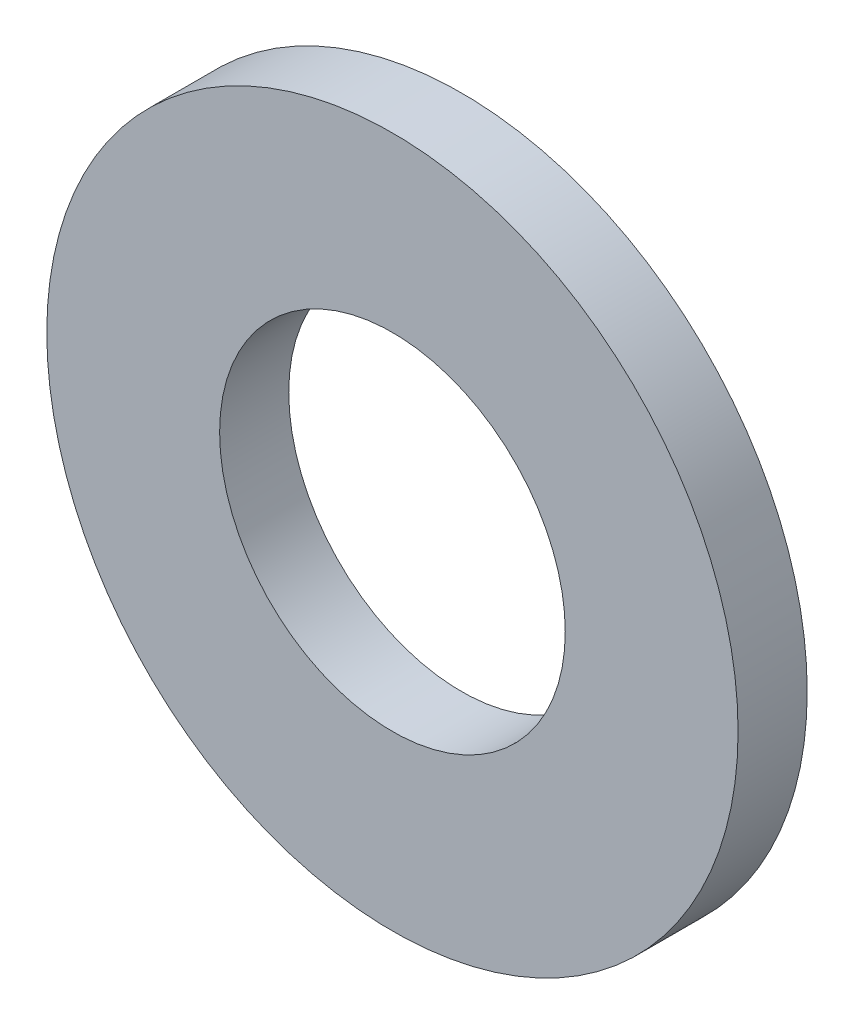
SolidWorks part; units mm, degrees
ref_plane "Front Plane" through (0, 0, 0) normal (0, 0, 1) x (1, 0, 0)
ref_plane "Top Plane" through (0, 0, 0) normal (0, 1, 0) x (1, 0, 0)
ref_plane "Right Plane" through (0, 0, 0) normal (1, 0, 0) x (0, 0, -1)
sketch "Sketch1" plane through (0, 0, 0) normal (0, 0, 1) x (1, 0, 0)
  circle A0 centre (0, 0) radius 4
  circle A1 centre (0, 0) radius 8
  dimension "D1" = 16
  dimension "D2" = 8
extrude "Boss-Extrude1" add sketch "Sketch1" along normal blind 1.6
